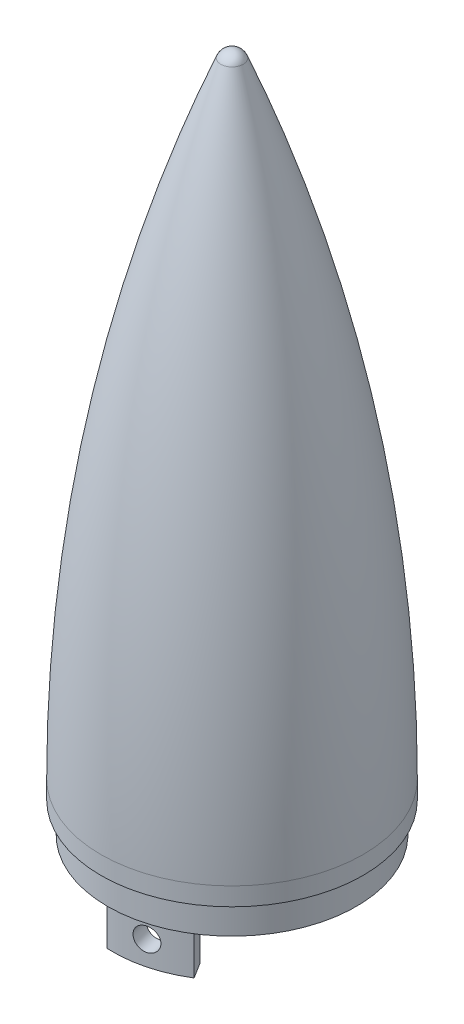
SolidWorks part; units mm, degrees
material "ABS"
ref_plane "Front Plane" through (0, 0, 0) normal (0, 0, 1) x (1, 0, 0)
ref_plane "Top Plane" through (0, 0, 0) normal (0, 1, 0) x (1, 0, 0)
ref_plane "Right Plane" through (0, 0, 0) normal (1, 0, 0) x (0, 0, -1)
sketch "Sketch1" plane through (0, 0, 0) normal (0, 1, 0) x (1, 0, 0)
  line L0 (0, 0) -> (27.6225, 0) construction
  circle A0 centre (0, 0) radius 27.6225
  circle A2 centre (0, 0) radius 25.0825
  point P6 (0, 0)
  dimension "D1" = 55.245
  dimension "D2" = 2.54
extrude "base" add sketch "Sketch1" along normal blind 3.81
sketch "Sketch2" plane through (0, 0, 0) normal (0, -1, 0) x (1, 0, 0)
  line L0 (0, 27.6225) -> (0, 0) construction
  line L1 (0, 0) -> (13.3917, 24.1592) construction
  line L2 (0, 27.6225) -> (0, 25.0825) construction
  line L3 (13.3917, 24.1592) -> (12.1602, 21.9376) construction
  line L5 (-1.3127, 25.0481) -> (0, 0) construction
  line L7 (13.2917, 21.2712) -> (0, 0) construction
  line L9 (13.2917, 21.2712) -> (11.2727, 18.0401)
  line L11 (-1.3127, 25.0481) -> (-1.1133, 21.2433)
  line L12 (0, 0) -> (6.9161, 26.7427) construction
  arc A0 (0, 27.6225) -> (13.3917, 24.1592) centre (0, 0) cw construction
  circle A2 centre (0, 0) radius 27.6225 construction
  arc A3 (0, 25.0825) -> (12.1602, 21.9376) centre (0, 0) cw construction
  circle A4 centre (0, 0) radius 25.0825 construction
  arc A9 (-1.3127, 25.0481) -> (13.2917, 21.2712) centre (0, 0) cw
  circle A10 centre (0, 0) radius 25.0825 construction
  arc A11 (-1.1133, 21.2433) -> (11.2727, 18.0401) centre (0, 0) cw
  circle M5 centre (0, 0) radius 25.0825
  dimension "D1" = 29
  dimension "D2" = 3.81
  dimension "D3" = 3
  dimension "D4" = 3
ref_plane "Plane1" through (0, 0, 0) normal (1, 0, 0) x (0, 0, -1)
sketch "Sketch4" plane through (0, 0, 0) normal (1, 0, 0) x (0, 0, -1)
  line L0 (-2.3596, 135.4489) -> (-2.3596, 129.0989) construction
  line L1 (25.0825, 3.81) -> (-25.0825, 3.81) construction
  line L2 (-27.6225, 3.81) -> (327.9775, 3.81) construction
  line L3 (-27.6225, 3.81) -> (27.6225, 3.81) construction
  line L6 (27.6225, 3.81) -> (-303.8475, 3.81) construction
  line L7 (27.6225, 3.81) -> (-27.6225, 3.81) construction
  line L9 (-27.6225, 3.81) -> (-25.0825, 3.81)
  line L10 (0, 3.81) -> (0, 137.0486) construction
  line L11 (0, 137.0486) -> (-13.758, 137.0486) construction
  line L12 (-2.3596, 129.0989) -> (0, 134.5086)
  line L13 (0, 137.0486) -> (0, 134.5086)
  arc A0 (-27.6225, 3.81) -> (-2.3596, 135.4489) centre (327.9775, 3.81) cw
  arc A1 (-25.0825, 3.81) -> (-2.3596, 129.0989) centre (331.6853, 3.81) cw
  arc A2 (0, 137.0486) -> (-2.3596, 135.4489) centre (0, 134.5086) ccw
  point P11 (-2.3596, 135.4489)
  dimension "D1" = 55.245
  dimension "D4" = 2.54
  dimension "D2" = 6.35
  dimension "D5" = 2.54
  dimension "D3" = 355.6
  dimension "D6" = 133.2386
revolve "Revolve1" add sketch "Sketch4" angle 360 about L10
extrude "bolt_point" add sketch "Sketch2" along normal blind 15.24 and the other way blind 12.7 contours L11 A11 L9 M5
pattern_circular "CirPattern2" count 2 over 360 about axis through (0, 0, 0) along (0, 1, 0) of "bolt_point"
chamfer "Chamfer1" distance 2.54 angle 45 2 edges at (5.3262, 12.7, 20.5949) (-5.3262, 12.7, -20.5949)
ref_plane "Plane2" through (6.9161, 0, 26.7427) normal (0.2504, 0, 0.9681) x (0.9681, 0, -0.2504)
sketch "Sketch5" plane through (6.9161, 0, 26.7427) normal (0.2504, 0, 0.9681) x (0.9681, 0, -0.2504)
  line L0 (0, 0) -> (0, -10.16) construction
  circle A0 centre (0, -10.16) radius 2.413
  circle A1 centre (0, -10.16) radius 2.54 construction
  dimension "D1" = 4.826
extrude "Cut-Extrude1" cut sketch "Sketch5" against normal up to surface (52.5887 mm away)
sketch "Sketch6" plane through (0, 0, 0) normal (0, -1, 0) x (1, 0, 0)
  circle A0 centre (0, 0) radius 25.0825
  circle A1 centre (0, 0) radius 26.2255
  arc A2 (1.3127, -25.0481) -> (13.2917, 21.2712) centre (0, 0) ccw construction
  dimension "D1" = 1.143
extrude "Boss-Extrude1" add sketch "Sketch6" along normal blind 6.35
